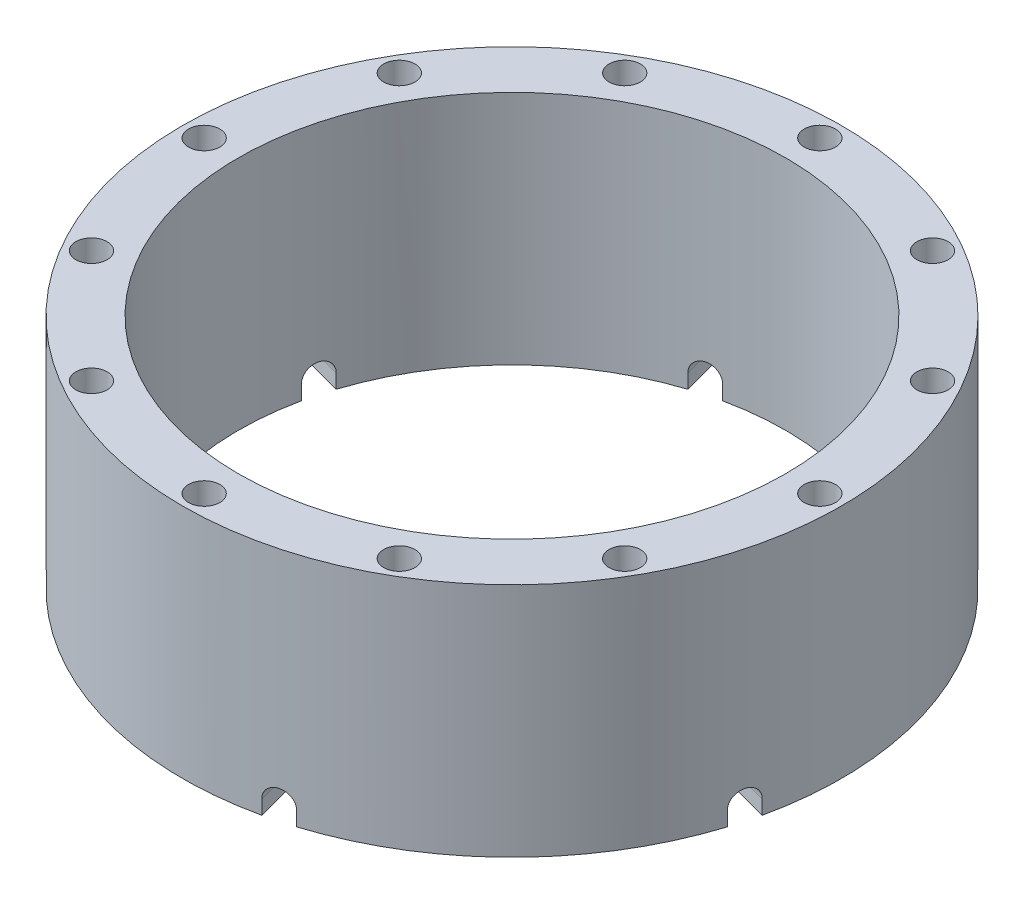
SolidWorks part; units mm, degrees
ref_plane "前视基准面" through (0, 0, 0) normal (0, 0, 1) x (1, 0, 0)
ref_plane "上视基准面" through (0, 0, 0) normal (0, 1, 0) x (1, 0, 0)
ref_plane "右视基准面" through (0, 0, 0) normal (1, 0, 0) x (0, 0, -1)
other "Configuration Table"
sketch "草图1" plane through (0, 0, 0) normal (0, 1, 0) x (1, 0, 0)
  circle A0 centre (0, 0) radius 57.8
  circle A1 centre (0, 0) radius 48
  dimension "D1" = 96
  dimension "D2" = 115.6
extrude "凸台-拉伸1" add sketch "草图1" along normal blind 41.4
sketch "草图2" plane through (0, 41.4, 0) normal (0, 1, 0) x (1, 0, 0)
  circle A0 centre (0, 0) radius 54 construction
  circle A1 centre (0, 54) radius 2.75
  dimension "D1" = 5.5
  dimension "D2" = 108
extrude "切除-拉伸1" cut sketch "草图2" against normal through all both and the other way through all
pattern_circular "阵列(圆周)1" count 12 over 360 about axis through (0, 0, 0) along (0, 1, 0) of "切除-拉伸1"
ref_plane "基准面1" through (0, 0, 0) normal (-0.7071, 0, 0.7071) x (0.7071, 0, 0.7071)
sketch "草图3" plane through (0, 0, 0) normal (-0.7071, 0, 0.7071) x (0.7071, 0, 0.7071)
  line L0 (-2.5, 5) -> (2.5, 5)
  line L1 (-2.5, 5) -> (-2.5, 0)
  line L2 (2.5, 5) -> (2.5, 0)
  line L3 (-2.5, 0) -> (2.5, 0)
  line L4 (-2.5, 5) -> (2.5, 0) construction
  line L5 (2.5, 5) -> (-2.5, 0) construction
  line L6 (-57.8, 0) -> (57.8, 0) construction
  circle A0 centre (0, 2.5) radius 2.5
  point P1 (0, 2.5)
  dimension "D1" = 5
  dimension "D2" = 5
extrude "切除-拉伸2" cut sketch "草图3" against normal through all contours A0 | A0 L3 L2 | A0 L1 L3
pattern_circular "阵列(圆周)2" count 6 over 360 about axis through (0, 0, 0) along (0, 1, 0) of "切除-拉伸2"
